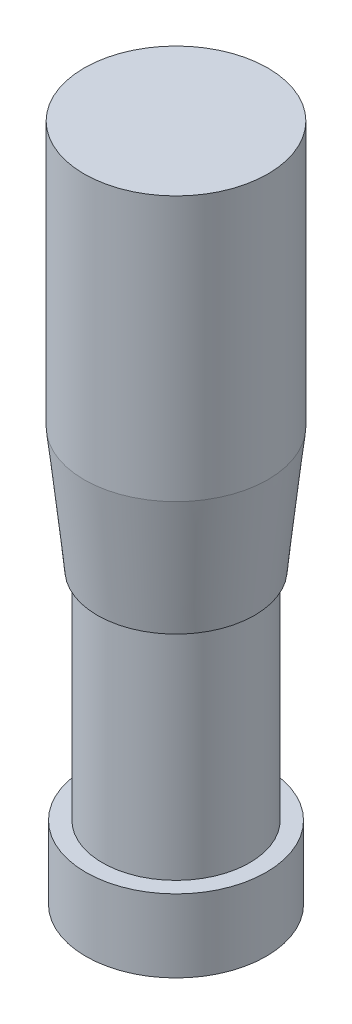
SolidWorks part; units mm, degrees
ref_plane "Front Plane" through (0, 0, 0) normal (0, 0, 1) x (1, 0, 0)
ref_plane "Top Plane" through (0, 0, 0) normal (0, 1, 0) x (1, 0, 0)
ref_plane "Right Plane" through (0, 0, 0) normal (1, 0, 0) x (0, 0, -1)
sketch "Sketch1" plane through (0, 0, 0) normal (0, 0, 1) x (1, 0, 0)
  line L0 (0, 0) -> (0, 62.1972) construction
  line L1 (0, 0) -> (-5.45, 0)
  line L2 (-5.45, 0) -> (-5.45, 4.4)
  line L3 (-5.45, 4.4) -> (-4.45, 4.4)
  line L4 (-4.45, 4.4) -> (-4.45, 17.5)
  line L6 (-5.55, 25) -> (-5.55, 41)
  line L7 (-5.55, 41) -> (0, 41)
  line L8 (0, 41) -> (0, 0)
  line L9 (-4.45, 17.5) -> (-4.75, 17.5)
  line L10 (-4.75, 17.5) -> (-5.55, 25)
  dimension "D1" = 41
  dimension "D2" = 5.45
  dimension "D3" = 4.45
  dimension "D4" = 4.4
  dimension "D5" = 17.5
  dimension "D6" = 5.55
  dimension "D7" = 0.3
  dimension "D8" = 25
revolve "Revolve1" add sketch "Sketch1" angle 360 about L0
